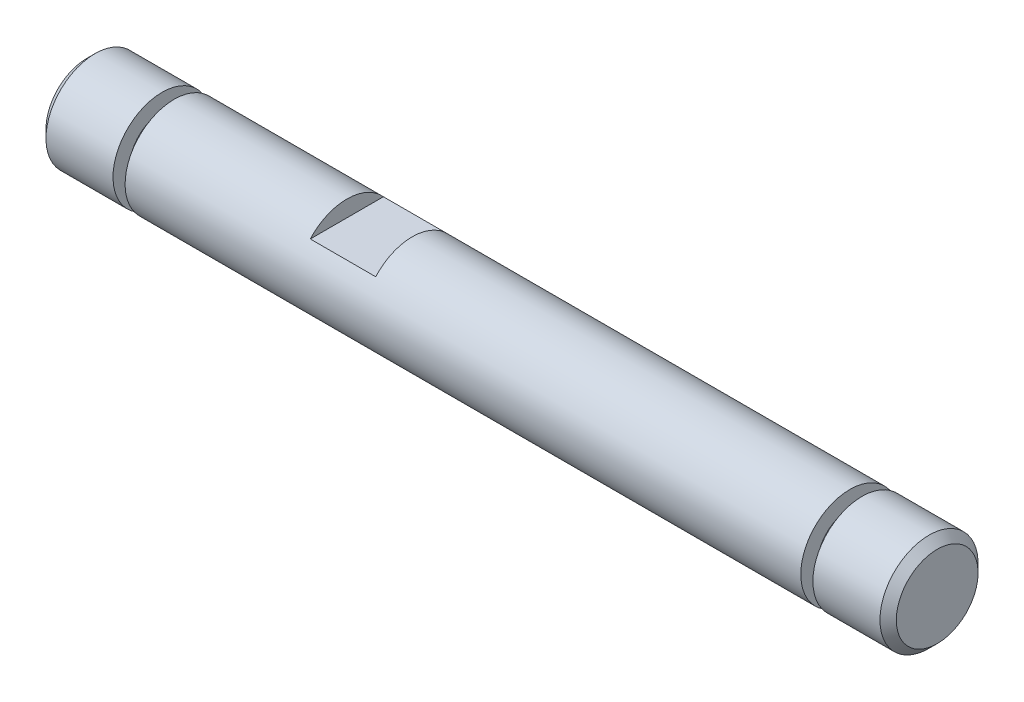
SolidWorks part; units mm, degrees
ref_plane "Plan de face" through (0, 0, 0) normal (0, 0, 1) x (1, 0, 0)
ref_plane "Plan de dessus" through (0, 0, 0) normal (0, 1, 0) x (1, 0, 0)
ref_plane "Plan de droite" through (0, 0, 0) normal (1, 0, 0) x (0, 0, -1)
sketch "Esquisse1" plane through (0, 0, 0) normal (0, 0, 1) x (1, 0, 0)
  line L0 (0, 0) -> (12.8037, 0) construction
  line L1 (0, 0) -> (0, 15.5366) construction
  line L2 (26, 0) -> (-26, 0)
  line L4 (-26, 0) -> (-26, 3)
  line L5 (-26, 3) -> (26, 3)
  line L6 (26, 0) -> (26, 3)
  point P10 (0, 0)
  dimension "D1" = 52
  dimension "D2" = 3
revolve "Révolution1" add sketch "Esquisse1" angle 360 about L0
chamfer "Chanfrein1" distance 0.5 angle 45 2 edges at (-26, 0, 3) (26, 0, 3)
sketch "Esquisse2" plane through (0, 0, 0) normal (0, 0, 1) x (1, 0, 0)
  line L0 (25.5, 3) -> (-25.5, 3) construction
  line L1 (25.5, 3) -> (-25.5, 3)
  line L3 (-10.1, 4) -> (-6.1, 4)
  line L4 (-10.1, 4) -> (-10.1, 2)
  line L5 (-10.1, 2) -> (-6.1, 2)
  line L6 (-6.1, 4) -> (-6.1, 2)
  line L7 (-10.1, 4) -> (-6.1, 2) construction
  line L8 (-10.1, 2) -> (-6.1, 4) construction
  point P2 (-8.1, 3)
  dimension "D1" = 1
  dimension "D2" = 8.1
  dimension "D3" = 4
extrude "Enlèv. mat.-Extru.1" cut sketch "Esquisse2" against normal through all both and the other way through all contours L5 L6 L3 L4
sketch "Esquisse3" plane through (0, 0, 0) normal (0, 0, 1) x (1, 0, 0)
  line L2 (-10.1, 3) -> (-25.5, 3) construction
  line L3 (-21.4, 3) -> (-20.66, 3)
  line L4 (0, 0) -> (0, 10.3249) construction
  line L5 (-21.4, 3) -> (-21.4, 2)
  line L6 (-21.4, 2) -> (-20.66, 2)
  line L7 (-20.66, 3) -> (-20.66, 2)
  line L8 (20.66, 3) -> (20.66, 2)
  line L9 (21.4, 2) -> (20.66, 2)
  line L10 (21.4, 3) -> (21.4, 2)
  line L11 (21.4, 3) -> (20.66, 3)
  line L17 (0, 0) -> (-35.8372, 0) construction
  dimension "D1" = 0.74
  dimension "D2" = 2
  dimension "D3" = 42.8
revolve "Enlèvement de matière-Révolution1" cut sketch "Esquisse3" angle 360 about L17
